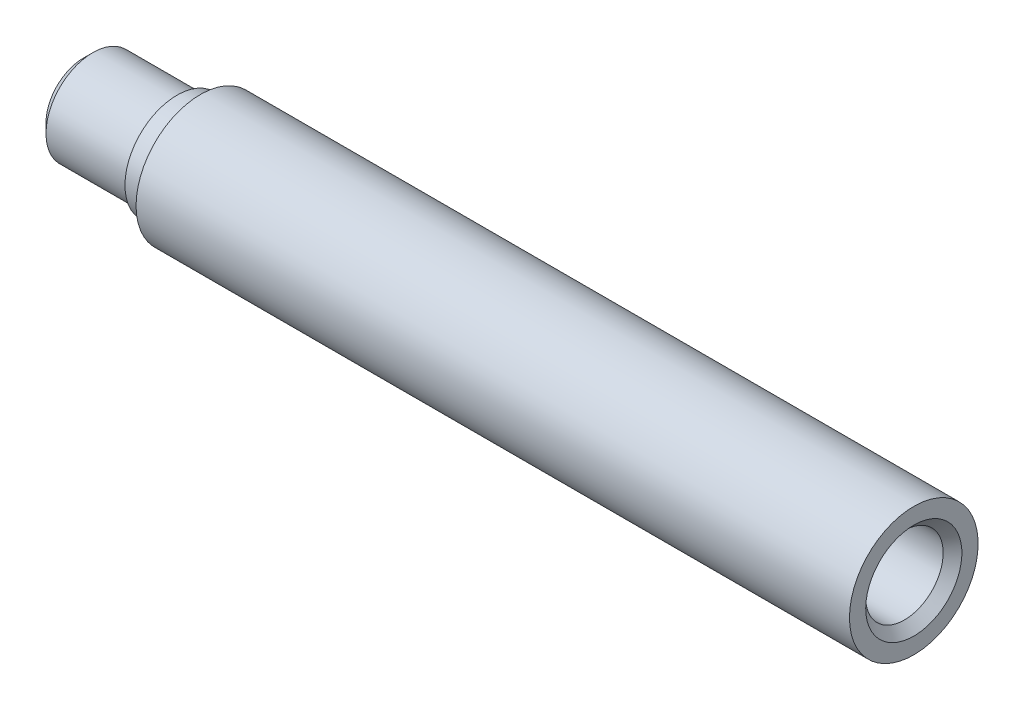
SolidWorks part; units mm, degrees
material "6061 Alloy"
ref_plane "Front Plane" through (0, 0, 0) normal (0, 0, 1) x (1, 0, 0)
ref_plane "Top Plane" through (0, 0, 0) normal (0, 1, 0) x (1, 0, 0)
ref_plane "Right Plane" through (0, 0, 0) normal (1, 0, 0) x (0, 0, -1)
ref_plane "Plane1" through (0, 0, 0) normal (0, 0, -1) x (-1, 0, 0)
sketch "Sketch1" plane through (0, 0, 0) normal (0, 0, -1) x (-1, 0, 0)
  line L0 (-19, 3.3114) -> (-17.0103, 0)
  line L1 (-17.0103, 0) -> (36, 0)
  line L2 (36, 0) -> (36, 3.2)
  line L3 (36, 3.2) -> (35.2, 4)
  line L4 (35.2, 4) -> (28, 4)
  line L5 (28, 4) -> (28, 4.45)
  line L6 (28, 4.45) -> (26, 4.45)
  line L7 (26, 4.45) -> (26, 5.5)
  line L8 (26, 5.5) -> (-35, 5.5)
  line L9 (-35, 5.5) -> (-35, 4.1114)
  line L10 (-35, 4.1114) -> (-34.2, 3.3114)
  line L11 (-34.2, 3.3114) -> (-19, 3.3114)
  line L12 (-35, 0) -> (36, 0) construction
  dimension "D1" = 5.5
revolve "Revolve1" add sketch "Sketch1" angle 360 about L12
cosmetic thread "Cosmetic Thread1" parameters "D1"=8, "D2"=6.891
cosmetic thread "Cosmetic Thread2" parameters "D1"=13, "D2"=8
